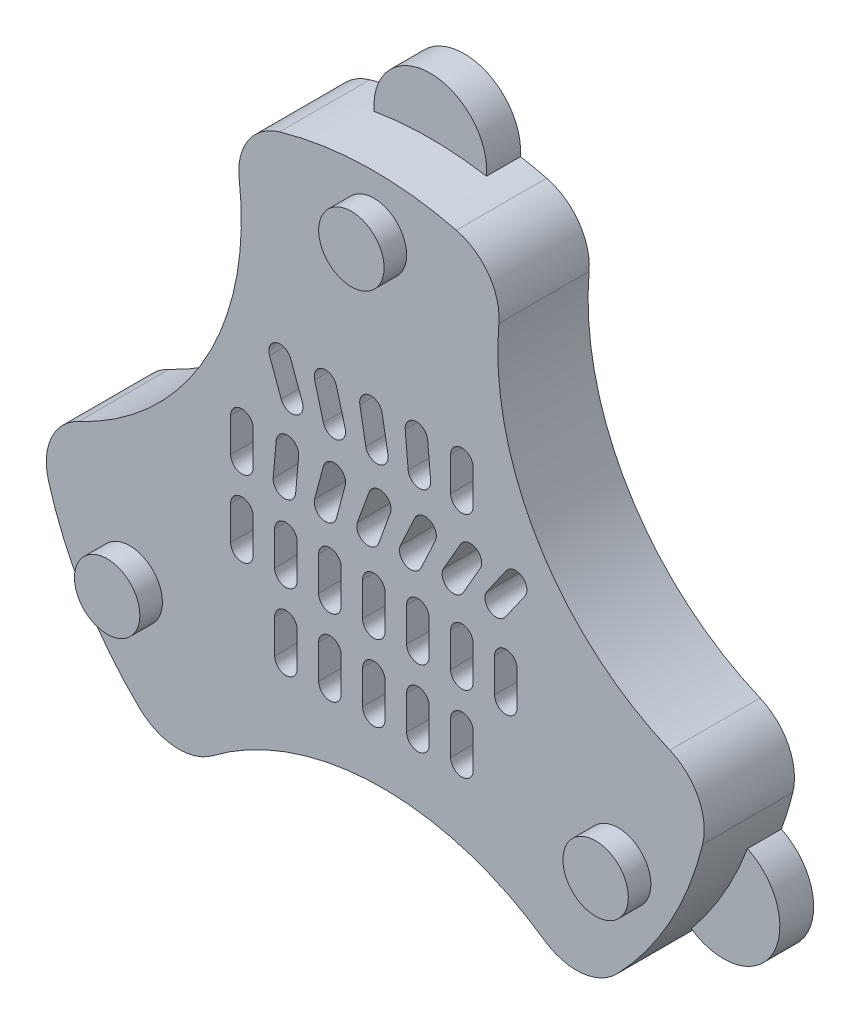
SolidWorks part; units mm, degrees
ref_plane "Спереди" through (0, 0, 0) normal (0, 0, 1) x (1, 0, 0)
ref_plane "Сверху" through (0, 0, 0) normal (0, 1, 0) x (1, 0, 0)
ref_plane "Справа" through (0, 0, 0) normal (1, 0, 0) x (0, 0, -1)
sketch "Sketch1" plane through (0, 0, 0) normal (0, 0, 1) x (1, 0, 0)
  line L0 (3.9, 6.755) -> (7.8, 0) construction
  line L2 (5.85, 10.1325) -> (11.7, 0) construction
  line L4 (7.8, 13.51) -> (15.6, 0) construction
  circle A61 centre (0, 0) radius 20
  circle A131 centre (0, 0) radius 1.25
  circle A484 centre (3.9, 0) radius 1.25
  circle A485 centre (7.8, 0) radius 1.25
  circle A486 centre (11.7, 0) radius 1.25
  circle A487 centre (15.6, 0) radius 1.25
  circle A488 centre (1.95, -3.3775) radius 1.25
  circle A489 centre (3.9, -6.755) radius 1.25
  circle A490 centre (5.85, -10.1325) radius 1.25
  circle A491 centre (7.8, -13.51) radius 1.25
  circle A492 centre (-1.95, -3.3775) radius 1.25
  circle A493 centre (-3.9, -6.755) radius 1.25
  circle A494 centre (-5.85, -10.1325) radius 1.25
  circle A495 centre (-7.8, -13.51) radius 1.25
  circle A496 centre (-3.9, 0) radius 1.25
  circle A497 centre (-7.8, 0) radius 1.25
  circle A498 centre (-11.7, 0) radius 1.25
  circle A499 centre (-15.6, 0) radius 1.25
  circle A500 centre (-1.95, 3.3775) radius 1.25
  circle A501 centre (-3.9, 6.755) radius 1.25
  circle A502 centre (-5.85, 10.1325) radius 1.25
  circle A503 centre (-7.8, 13.51) radius 1.25
  circle A504 centre (1.95, 3.3775) radius 1.25
  circle A505 centre (3.9, 6.755) radius 1.25
  circle A506 centre (5.85, 10.1325) radius 1.25
  circle A507 centre (7.8, 13.51) radius 1.25
  circle A508 centre (5.85, 3.3775) radius 1.25
  circle A509 centre (7.8, 6.755) radius 1.25
  circle A510 centre (9.75, 3.3775) radius 1.25
  circle A511 centre (11.7, 6.755) radius 1.25
  circle A512 centre (9.7491, 10.1341) radius 1.25
  circle A513 centre (13.6509, 3.3759) radius 1.25
  circle A514 centre (5.85, -3.3791) radius 1.25
  circle A515 centre (9.75, -3.3791) radius 1.25
  circle A516 centre (7.8, -6.7566) radius 1.25
  circle A517 centre (11.7, -6.7566) radius 1.25
  circle A518 centre (9.7491, -10.1356) radius 1.25
  circle A519 centre (13.6509, -3.3775) radius 1.25
  circle A520 centre (-0.0013, -6.7573) radius 1.25
  circle A521 centre (1.9487, -10.1348) radius 1.25
  circle A522 centre (-1.9513, -10.1348) radius 1.25
  circle A523 centre (-0.0013, -13.5123) radius 1.25
  circle A524 centre (-3.9032, -13.5123) radius 1.25
  circle A525 centre (3.9005, -13.5123) radius 1.25
  circle A526 centre (-5.8527, -3.3791) radius 1.25
  circle A527 centre (-7.8027, -6.7566) radius 1.25
  circle A528 centre (-9.7527, -3.3791) radius 1.25
  circle A529 centre (-11.7027, -6.7566) radius 1.25
  circle A530 centre (-13.6536, -3.3775) radius 1.25
  circle A531 centre (-9.7518, -10.1356) radius 1.25
  circle A532 centre (-5.8527, 3.3775) radius 1.25
  circle A533 centre (-9.7527, 3.3775) radius 1.25
  circle A534 centre (-7.8027, 6.755) radius 1.25
  circle A535 centre (-11.7027, 6.755) radius 1.25
  circle A536 centre (-9.7518, 10.1341) radius 1.25
  circle A537 centre (-13.6536, 3.3759) radius 1.25
  circle A538 centre (-0.0014, 6.7558) radius 1.25
  circle A539 centre (-1.9514, 10.1333) radius 1.25
  circle A540 centre (1.9486, 10.1333) radius 1.25
  circle A541 centre (-0.0014, 13.5108) radius 1.25
  circle A542 centre (3.9005, 13.5108) radius 1.25
  circle A543 centre (-3.9032, 13.5108) radius 1.25
  circle A544 centre (13.65, -1.1258) radius 2.2517 construction
  circle A545 centre (11.7009, -4.5044) radius 2.2522 construction
  circle A546 centre (9.75, -7.8834) radius 2.2522 construction
  circle A547 centre (7.7987, -11.2591) radius 2.2509 construction
  circle A548 centre (13.65, -1.1258) radius 0.65
  circle A549 centre (11.7009, -4.5044) radius 0.65
  circle A550 centre (9.75, -7.8834) radius 0.65
  circle A551 centre (7.7987, -11.2591) radius 0.65
  circle A552 centre (9.75, -1.1258) radius 0.65
  circle A553 centre (7.8009, -4.5044) radius 0.65
  circle A554 centre (5.85, -7.8834) radius 0.65
  circle A555 centre (3.8987, -11.2591) radius 0.65
  circle A556 centre (5.85, -1.1258) radius 0.65
  circle A557 centre (3.9009, -4.5044) radius 0.65
  circle A558 centre (1.95, -7.8834) radius 0.65
  circle A559 centre (-0.0013, -11.2591) radius 0.65
  circle A560 centre (1.95, -1.1258) radius 0.65
  circle A561 centre (0.0009, -4.5044) radius 0.65
  circle A562 centre (-1.95, -7.8834) radius 0.65
  circle A563 centre (-3.9013, -11.2591) radius 0.65
  circle A564 centre (-1.95, -1.1258) radius 0.65
  circle A565 centre (-3.8991, -4.5044) radius 0.65
  circle A566 centre (-5.85, -7.8834) radius 0.65
  circle A567 centre (-7.8013, -11.2591) radius 0.65
  circle A568 centre (-5.85, -1.1258) radius 0.65
  circle A569 centre (-7.7991, -4.5044) radius 0.65
  circle A570 centre (-9.75, -7.8834) radius 0.65
  circle A572 centre (-9.75, -1.1258) radius 0.65
  circle A573 centre (-11.6991, -4.5044) radius 0.65
  circle A576 centre (-13.65, -1.1258) radius 0.65
  circle A587 centre (0, 2.2517) radius 2.2517 construction
  circle A588 centre (0, 2.2517) radius 0.65
  circle A589 centre (3.9, 2.2517) radius 0.65
  circle A590 centre (7.8, 2.2517) radius 0.65
  circle A591 centre (11.7, 2.2517) radius 0.65
  circle A592 centre (15.6, 2.2517) radius 0.65
  circle A593 centre (1.9491, 5.6297) radius 2.2522 construction
  circle A594 centre (1.9491, 5.6297) radius 0.65
  circle A595 centre (5.8491, 5.6297) radius 0.65
  circle A596 centre (9.7491, 5.6297) radius 0.65
  circle A597 centre (13.6491, 5.6297) radius 0.65
  circle A598 centre (3.8991, 9.0072) radius 2.2522 construction
  circle A599 centre (3.8991, 9.0072) radius 0.65
  circle A600 centre (7.7991, 9.0072) radius 0.65
  circle A601 centre (11.6991, 9.0072) radius 0.65
  circle A602 centre (5.85, 12.3842) radius 2.2517 construction
  circle A603 centre (5.85, 12.3842) radius 0.65
  circle A604 centre (9.75, 12.3842) radius 0.65
  circle A605 centre (5.85, -14.6358) radius 0.65
  circle A606 centre (1.9509, -14.6353) radius 0.65
  circle A607 centre (-1.9491, -14.6353) radius 0.65
  circle A608 centre (-5.85, -14.6358) radius 0.65
  circle A609 centre (-15.6, 2.2517) radius 0.65
  circle A610 centre (-13.65, 5.6281) radius 0.65
  circle A611 centre (-11.7, 9.0056) radius 0.65
  circle A612 centre (-9.75, 12.3842) radius 0.65
  circle A613 centre (-5.85, 12.3842) radius 0.65
  circle A614 centre (-1.95, 12.3842) radius 0.65
  circle A615 centre (1.95, 12.3842) radius 0.65
  circle A616 centre (-7.8, 9.0056) radius 0.65
  circle A617 centre (-9.75, 5.6281) radius 0.65
  circle A618 centre (-11.7, 2.2517) radius 0.65
  circle A619 centre (-3.9, 9.0056) radius 0.65
  circle A620 centre (-5.85, 5.6281) radius 0.65
  circle A621 centre (-7.8, 2.2517) radius 0.65
  circle A622 centre (0, 9.0056) radius 0.65
  circle A623 centre (-1.95, 5.6281) radius 0.65
  circle A624 centre (-3.9, 2.2517) radius 0.65
  circle A625 centre (-15.5991, -4.5044) radius 0.65
  circle A626 centre (-13.65, -7.8834) radius 0.65
  circle A627 centre (-17.55, -7.8834) radius 0.65
  circle A628 centre (-19.5013, -11.2591) radius 0.65
  circle A629 centre (-15.6013, -11.2591) radius 0.65
  circle A630 centre (-11.7013, -11.2591) radius 0.65
  point P51 (0, 0)
  point P125 (-0.0013, -0.0008)
  point P231 (0, 0)
  dimension "D1" = 5
  dimension "D3" = 6
  dimension "D5" = 8
  dimension "D7" = 4
  dimension "D11" = 4
  dimension "D2" = 6
  dimension "D6" = 5
  dimension "D8" = 3
  dimension "D9" = 2
  dimension "D4" = 1.3
  dimension "D10" = 3
ref_plane "Plane1" through (0, 0, 10) normal (0, 0, 1) x (1, 0, 0)
sketch "Sketch2" plane through (0, 0, 10) normal (0, 0, 1) x (1, 0, 0)
  line L2 (8.0291, 21.9345) -> (-10.7971, 21.9345) construction
  circle A52 centre (0, 0) radius 16.85 construction
  circle A53 centre (0, 0) radius 18.85
  point P0 (0, 0)
  point P10 (0, 0)
  point P11 (0, 0)
  line B0 (4.7641, 11.7139) -> (5.0256, 8.7254)
  arc B1 (3.0332, 8.551) -> (5.0256, 8.7254) centre (4.0294, 8.6382) ccw
  line B2 (2.7717, 11.5396) -> (3.0332, 8.551)
  arc B3 (4.7641, 11.7139) -> (2.7717, 11.5396) centre (3.7679, 11.6268) ccw
  line B4 (3.7679, 11.6268) -> (4.0294, 8.6382) construction
  line B5 (0.722, 11.7838) -> (1.2429, 8.8293)
  arc B6 (-0.7267, 8.482) -> (1.2429, 8.8293) centre (0.2581, 8.6557) ccw
  line B7 (-1.2476, 11.4365) -> (-0.7267, 8.482)
  arc B8 (0.722, 11.7838) -> (-1.2476, 11.4365) centre (-0.2628, 11.6101) ccw
  line B9 (-0.2628, 11.6101) -> (0.2581, 8.6557) construction
  line B10 (-3.3247, 11.8406) -> (-2.5482, 8.9428)
  arc B11 (-4.48, 8.4252) -> (-2.5482, 8.9428) centre (-3.5141, 8.684) ccw
  line B12 (-5.2565, 11.323) -> (-4.48, 8.4252)
  arc B13 (-3.3247, 11.8406) -> (-5.2565, 11.323) centre (-4.2906, 11.5818) ccw
  line B14 (-4.2906, 11.5818) -> (-3.5141, 8.684) construction
  line B15 (-7.3747, 11.8841) -> (-6.3486, 9.065)
  arc B16 (-8.228, 8.3809) -> (-6.3486, 9.065) centre (-7.2883, 8.723) ccw
  line B17 (-9.2541, 11.2) -> (-8.228, 8.3809)
  arc B18 (-7.3747, 11.8841) -> (-9.2541, 11.2) centre (-8.3144, 11.542) ccw
  line B19 (-8.3144, 11.542) -> (-7.2883, 8.723) construction
  line B20 (10.0165, 2.7228) -> (11.7373, 5.1803)
  arc B21 (13.3756, 4.0332) -> (11.7373, 5.1803) centre (12.5564, 4.6067) ccw
  line B22 (11.6548, 1.5757) -> (13.3756, 4.0332)
  arc B23 (10.0165, 2.7228) -> (11.6548, 1.5757) centre (10.8357, 2.1493) ccw
  line B24 (10.8357, 2.1493) -> (12.5564, 4.6067) construction
  line B25 (6.18, 2.579) -> (7.68, 5.177)
  arc B26 (9.4121, 4.177) -> (7.68, 5.177) centre (8.546, 4.677) ccw
  line B27 (7.9121, 1.579) -> (9.4121, 4.177)
  arc B28 (6.18, 2.579) -> (7.9121, 1.579) centre (7.046, 2.079) ccw
  line B29 (7.046, 2.079) -> (8.546, 4.677) construction
  line B30 (2.3558, 2.4412) -> (3.6237, 5.1601)
  arc B31 (5.4363, 4.3148) -> (3.6237, 5.1601) centre (4.53, 4.7375) ccw
  line B32 (4.1684, 1.5959) -> (5.4363, 4.3148)
  arc B33 (2.3558, 2.4412) -> (4.1684, 1.5959) centre (3.2621, 2.0185) ccw
  line B34 (3.2621, 2.0185) -> (4.53, 4.7375) construction
  line B35 (-1.4567, 2.3105) -> (-0.4306, 5.1296)
  arc B36 (1.4488, 4.4455) -> (-0.4306, 5.1296) centre (0.5091, 4.7875) ccw
  line B37 (0.4227, 1.6264) -> (1.4488, 4.4455)
  arc B38 (-1.4567, 2.3105) -> (0.4227, 1.6264) centre (-0.517, 1.9685) ccw
  line B39 (-0.517, 1.9685) -> (0.5091, 4.7875) construction
  line B40 (-5.2581, 2.1879) -> (-4.4816, 5.0857)
  arc B41 (-2.5498, 4.5681) -> (-4.4816, 5.0857) centre (-3.5157, 4.8269) ccw
  line B42 (-3.3263, 1.6703) -> (-2.5498, 4.5681)
  arc B43 (-5.2581, 2.1879) -> (-3.3263, 1.6703) centre (-4.2922, 1.9291) ccw
  line B44 (-4.2922, 1.9291) -> (-3.5157, 4.8269) construction
  line B45 (-8.9296, 1.9704) -> (-8.6682, 4.9589)
  arc B46 (-6.6758, 4.7846) -> (-8.6682, 4.9589) centre (-7.672, 4.8718) ccw
  line B47 (-6.9372, 1.7961) -> (-6.6758, 4.7846)
  arc B48 (-8.9296, 1.9704) -> (-6.9372, 1.7961) centre (-7.9334, 1.8832) ccw
  line B49 (-7.9334, 1.8832) -> (-7.672, 4.8718) construction
  line B50 (-12.704, 1.878) -> (-12.704, 4.878)
  arc B51 (-10.704, 4.878) -> (-12.704, 4.878) centre (-11.704, 4.878) ccw
  line B52 (-10.704, 1.878) -> (-10.704, 4.878)
  arc B53 (-12.704, 1.878) -> (-10.704, 1.878) centre (-11.704, 1.878) ccw
  line B54 (-11.704, 1.878) -> (-11.704, 4.878) construction
  line B55 (10.6941, -4.8778) -> (10.6941, -1.8778)
  arc B56 (12.6941, -1.8778) -> (10.6941, -1.8778) centre (11.6941, -1.8778) ccw
  line B57 (12.6941, -4.8778) -> (12.6941, -1.8778)
  arc B58 (10.6941, -4.8778) -> (12.6941, -4.8778) centre (11.6941, -4.8778) ccw
  line B59 (6.7941, -4.8778) -> (6.7941, -1.8778)
  arc B60 (8.7941, -1.8778) -> (6.7941, -1.8778) centre (7.7941, -1.8778) ccw
  line B61 (8.7941, -4.8778) -> (8.7941, -1.8778)
  arc B62 (6.7941, -4.8778) -> (8.7941, -4.8778) centre (7.7941, -4.8778) ccw
  line B63 (2.8941, -4.8778) -> (2.8941, -1.8778)
  arc B64 (4.8941, -1.8778) -> (2.8941, -1.8778) centre (3.8941, -1.8778) ccw
  line B65 (4.8941, -4.8778) -> (4.8941, -1.8778)
  arc B66 (2.8941, -4.8778) -> (4.8941, -4.8778) centre (3.8941, -4.8778) ccw
  line B67 (-1.0059, -4.8778) -> (-1.0059, -1.8778)
  arc B68 (0.9941, -1.8778) -> (-1.0059, -1.8778) centre (-0.0059, -1.8778) ccw
  line B69 (0.9941, -4.8778) -> (0.9941, -1.8778)
  arc B70 (-1.0059, -4.8778) -> (0.9941, -4.8778) centre (-0.0059, -4.8778) ccw
  line B71 (-4.9059, -4.8778) -> (-4.9059, -1.8778)
  arc B72 (-2.9059, -1.8778) -> (-4.9059, -1.8778) centre (-3.9059, -1.8778) ccw
  line B73 (-2.9059, -4.8778) -> (-2.9059, -1.8778)
  arc B74 (-4.9059, -4.8778) -> (-2.9059, -4.8778) centre (-3.9059, -4.8778) ccw
  line B75 (-8.8046, -4.8778) -> (-8.8008, -1.8778)
  arc B76 (-6.8008, -1.8804) -> (-8.8008, -1.8778) centre (-7.8008, -1.8791) ccw
  line B77 (-6.8046, -4.8804) -> (-6.8008, -1.8804)
  arc B78 (-8.8046, -4.8778) -> (-6.8046, -4.8804) centre (-7.8046, -4.8791) ccw
  line B79 (-12.7059, -4.8778) -> (-12.7059, -1.8778)
  arc B80 (-10.7059, -1.8778) -> (-12.7059, -1.8778) centre (-11.7059, -1.8778) ccw
  line B81 (-10.7059, -4.8778) -> (-10.7059, -1.8778)
  arc B82 (-12.7059, -4.8778) -> (-10.7059, -4.8778) centre (-11.7059, -4.8778) ccw
  line B83 (8.7993, -8.6356) -> (8.7993, -11.6356)
  arc B84 (6.7993, -11.6356) -> (8.7993, -11.6356) centre (7.7993, -11.6356) ccw
  line B85 (6.7993, -8.6356) -> (6.7993, -11.6356)
  arc B86 (8.7993, -8.6356) -> (6.7993, -8.6356) centre (7.7993, -8.6356) ccw
  line B87 (4.8993, -8.6356) -> (4.8993, -11.6356)
  arc B88 (2.8993, -11.6356) -> (4.8993, -11.6356) centre (3.8993, -11.6356) ccw
  line B89 (2.8993, -8.6356) -> (2.8993, -11.6356)
  arc B90 (4.8993, -8.6356) -> (2.8993, -8.6356) centre (3.8993, -8.6356) ccw
  line B91 (0.9993, -8.6356) -> (0.9993, -11.6356)
  arc B92 (-1.0007, -11.6356) -> (0.9993, -11.6356) centre (-0.0007, -11.6356) ccw
  line B93 (-1.0007, -8.6356) -> (-1.0007, -11.6356)
  arc B94 (0.9993, -8.6356) -> (-1.0007, -8.6356) centre (-0.0007, -8.6356) ccw
  line B95 (-2.9007, -8.6356) -> (-2.9007, -11.6356)
  arc B96 (-4.9007, -11.6356) -> (-2.9007, -11.6356) centre (-3.9007, -11.6356) ccw
  line B97 (-4.9007, -8.6356) -> (-4.9007, -11.6356)
  arc B98 (-2.9007, -8.6356) -> (-4.9007, -8.6356) centre (-3.9007, -8.6356) ccw
  line B99 (-6.8007, -8.6356) -> (-6.8007, -11.6356)
  arc B100 (-8.8007, -11.6356) -> (-6.8007, -11.6356) centre (-7.8007, -11.6356) ccw
  line B101 (-8.8007, -8.6356) -> (-8.8007, -11.6356)
  arc B102 (-6.8007, -8.6356) -> (-8.8007, -8.6356) centre (-7.8007, -8.6356) ccw
  line B103 (8.7976, 11.6329) -> (8.7976, 8.6329)
  arc B104 (6.7976, 8.6329) -> (8.7976, 8.6329) centre (7.7976, 8.6329) ccw
  line B105 (6.7976, 11.6329) -> (6.7976, 8.6329)
  arc B106 (8.7976, 11.6329) -> (6.7976, 11.6329) centre (7.7976, 11.6329) ccw
  dimension "D15" = 2
  dimension "D2" = 95
  dimension "D4" = 105
  dimension "D5" = 110
  dimension "D6" = 55
  dimension "D7" = 60
  dimension "D9" = 70
  dimension "D12" = 90
  dimension "D3" = 100
  dimension "D8" = 65
  dimension "D10" = 75
  dimension "D11" = 85
sketch_block_instance "Block4-1"
sketch_block "Block4"
sketch_block_instance "Block5-1"
sketch_block "Block5"
sketch_block_instance "Block6-1"
sketch_block "Block6"
sketch_block_instance "Block7-1"
sketch_block "Block7" parameters "D1"=2, "D2"=3
sketch_block_instance "Block8-1"
sketch_block "Block8"
sketch_block_instance "Block9-1"
sketch_block "Block9"
sketch_block_instance "Block10-1"
sketch_block "Block10"
sketch_block_instance "Block11-1"
sketch_block "Block11"
sketch_block_instance "Block12-1"
sketch_block "Block12"
sketch_block_instance "Block13-1"
sketch_block "Block13" parameters "D1"=2, "D2"=3
sketch_block_instance "Block14-1"
sketch_block "Block14"
sketch_block_instance "Block15-1"
sketch_block "Block15"
sketch_block_instance "Block16-1"
sketch_block "Block16"
sketch_block_instance "Block17-1"
sketch_block "Block17"
sketch_block_instance "Block18-1"
sketch_block "Block18"
sketch_block_instance "Block19-1"
sketch_block "Block19"
sketch_block_instance "Block20-1"
sketch_block "Block20" parameters "D1"=3, "D2"=2
sketch_block_instance "Block21-1"
sketch_block "Block21"
sketch_block_instance "Block22-1"
sketch_block "Block22"
sketch_block_instance "Block23-1"
sketch_block "Block23"
sketch_block_instance "Block24-1"
sketch_block "Block24"
sketch_block_instance "Block25-1"
sketch_block "Block25"
sketch_block_instance "Block26-1"
sketch_block "Block26" parameters "D1"=3, "D2"=2
sketch_block_instance "Block28-1"
sketch_block "Block28"
extrude "Boss-Extrude1" add sketch "Sketch2" along normal blind 8
sketch "Sketch3" plane through (0, 0, 18) normal (0, 0, 1) x (1, 0, 0)
  circle A0 centre (0, 0) radius 17.6
  circle A1 centre (0, 0) radius 30
extrude "Boss-Extrude2" add sketch "Sketch3" against normal up to surface (8 mm away) up to face at (-7.8007, -10.1356, 10)
sketch "Sketch4" plane through (0, 0, 18) normal (0, 0, 1) x (1, 0, 0)
  circle A0 centre (0, 0) radius 25 construction
  circle A1 centre (0, 25) radius 2.9
  circle A2 centre (21.6506, -12.5) radius 2.9
  circle A3 centre (-21.6506, -12.5) radius 2.9
  point P11 (0, 0)
  dimension "D1" = 3
extrude "Boss-Extrude3" add sketch "Sketch4" along normal blind 2
sketch "Sketch6" plane through (0, 0, 10) normal (0, 0, -1) x (-1, 0, 0)
  circle A0 centre (0, 30) radius 5
  circle A1 centre (0, 0) radius 30 construction
  circle A2 centre (25.9808, -15) radius 5
  circle A3 centre (-25.9808, -15) radius 5
  point P10 (0, 0)
  dimension "D1" = 3
extrude "Boss-Extrude4" add sketch "Sketch6" against normal blind 3
sketch "Sketch5" plane through (0, 0, 10) normal (0, 0, -1) x (-1, 0, 0)
  circle A0 centre (0, 25) radius 3
  circle A1 centre (21.6506, -12.5) radius 3
  circle A2 centre (-21.6506, -12.5) radius 3
extrude "Cut-Extrude1" cut sketch "Sketch5" against normal blind 3
sketch "Sketch7" plane through (0, 0, 10) normal (0, 0, -1) x (-1, 0, 0)
  line L0 (0, 0) -> (-35.9801, 21.6664) construction
  circle A0 centre (0, 0) radius 42 construction
  circle A1 centre (-35.9801, 21.6664) radius 25
  circle A2 centre (36.7537, 20.3265) radius 25
  circle A3 centre (-0.7736, -41.9929) radius 25
  point P11 (0, 0)
  dimension "D1" = 3
extrude "Cut-Extrude2" cut sketch "Sketch7" against normal blind 8
fillet "Fillet1" radius 5 6 edges at (-29.7735, -3.6793, 14) (-12.7099, 27.1746, 14) (18.0731, -23.945, 14) (-17.1789, -24.5944, 14) (11.7004, 27.6243, 14) (29.8888, -2.5802, 14)
sketch "Sketch8"
sketch_block_instance "Block1-1"
sketch_block "Block1" parameters "D1"=2, "D2"=3
sketch_block_instance "Block3-1"
sketch_block "Block3" parameters "D1"=2, "D2"=3
sketch "Sketch9" plane through (0, 0, 0) normal (0, 0, 1) x (1, 0, 0)
  line L0 (-7.8, 13.51) -> (-7.8027, 6.755) construction
  line L1 (-9.7518, 10.1341) -> (-5.85, 10.1325) construction
  line L2 (-7.8008, 11.6325) -> (-7.8019, 8.6325) construction
  line L3 (-6.8008, 11.6321) -> (-6.8019, 8.6321)
  line L4 (-8.8008, 11.6329) -> (-8.8019, 8.6329)
  line L5 (-4.9008, 11.6329) -> (-4.9019, 8.6329)
  line L6 (-2.9008, 11.6321) -> (-2.9019, 8.6321)
  line L7 (-3.9008, 11.6325) -> (-3.9019, 8.6325) construction
  line L8 (-1.0008, 11.6329) -> (-1.0019, 8.6329)
  line L9 (0.9992, 11.6321) -> (0.9981, 8.6321)
  line L10 (-0.0008, 11.6325) -> (-0.0019, 8.6325) construction
  line L11 (2.8992, 11.6329) -> (2.8981, 8.6329)
  line L12 (4.8992, 11.6321) -> (4.8981, 8.6321)
  line L13 (3.8992, 11.6325) -> (3.8981, 8.6325) construction
  line L14 (6.7992, 11.6329) -> (6.7981, 8.6329)
  line L15 (8.7992, 11.6321) -> (8.7981, 8.6321)
  line L16 (7.7992, 11.6325) -> (7.7981, 8.6325) construction
  line L17 (-9.7518, 10.1341) -> (-9.7527, 3.3775) construction
  line L18 (-11.7027, 6.755) -> (-7.8027, 6.755) construction
  line L19 (-10.7035, 1.877) -> (-10.702, 4.877)
  line L22 (-9.7527, 3.3775) -> (-5.8527, 3.3775) construction
  line L25 (-7.8027, 6.755) -> (-7.8, 0) construction
  line L26 (-7.8035, 1.8775) -> (-7.8019, 4.8775) construction
  line L27 (-8.8035, 1.878) -> (-8.8019, 4.878)
  line L28 (-6.8035, 1.877) -> (-6.8019, 4.877)
  line L29 (-2.9035, 1.877) -> (-2.9019, 4.877)
  line L30 (-4.9035, 1.878) -> (-4.9019, 4.878)
  line L31 (-3.9035, 1.8775) -> (-3.9019, 4.8775) construction
  line L32 (0.9965, 1.877) -> (0.9981, 4.877)
  line L33 (-1.0035, 1.878) -> (-1.0019, 4.878)
  line L34 (-0.0035, 1.8775) -> (-0.0019, 4.8775) construction
  line L35 (4.8965, 1.877) -> (4.8981, 4.877)
  line L36 (2.8965, 1.878) -> (2.8981, 4.878)
  line L37 (3.8965, 1.8775) -> (3.8981, 4.8775) construction
  line L38 (8.7965, 1.877) -> (8.7981, 4.877)
  line L39 (6.7965, 1.878) -> (6.7981, 4.878)
  line L40 (7.7965, 1.8775) -> (7.7981, 4.8775) construction
  line L41 (12.6965, 1.877) -> (12.6981, 4.877)
  line L42 (10.6965, 1.878) -> (10.6981, 4.878)
  line L43 (11.6965, 1.8775) -> (11.6981, 4.8775) construction
  line L44 (-12.7035, 1.878) -> (-12.7019, 4.878)
  line L45 (-11.7035, 1.8775) -> (-11.702, 4.8775) construction
  line L46 (-9.7527, -3.3791) -> (-5.8527, -3.3791) construction
  line L47 (-7.8, 0) -> (-7.8027, -6.7566) construction
  line L48 (-7.8046, -4.8791) -> (-7.8008, -1.8791) construction
  line L49 (-8.8046, -4.8778) -> (-8.8008, -1.8778)
  line L50 (-6.8046, -4.8804) -> (-6.8008, -1.8804)
  line L51 (-2.9046, -4.8804) -> (-2.9008, -1.8804)
  line L52 (-4.9046, -4.8778) -> (-4.9008, -1.8778)
  line L53 (-3.9046, -4.8791) -> (-3.9008, -1.8791) construction
  line L54 (0.9954, -4.8804) -> (0.9992, -1.8804)
  line L55 (-1.0046, -4.8778) -> (-1.0008, -1.8778)
  line L56 (-0.0046, -4.8791) -> (-0.0008, -1.8791) construction
  line L57 (4.8954, -4.8804) -> (4.8992, -1.8804)
  line L58 (2.8954, -4.8778) -> (2.8992, -1.8778)
  line L59 (3.8954, -4.8791) -> (3.8992, -1.8791) construction
  line L60 (8.7954, -4.8804) -> (8.7992, -1.8804)
  line L61 (6.7954, -4.8778) -> (6.7992, -1.8778)
  line L62 (7.7954, -4.8791) -> (7.7992, -1.8791) construction
  line L63 (12.6954, -4.8804) -> (12.6992, -1.8804)
  line L64 (10.6954, -4.8778) -> (10.6992, -1.8778)
  line L65 (11.6954, -4.8791) -> (11.6992, -1.8791) construction
  line L66 (-10.7046, -4.8804) -> (-10.7008, -1.8804)
  line L67 (-12.7046, -4.8778) -> (-12.7008, -1.8778)
  line L68 (-11.7046, -4.8791) -> (-11.7008, -1.8791) construction
  line L69 (-9.7518, -10.1356) -> (-5.482, -10.1356) construction
  line L70 (-7.8027, -6.7566) -> (-7.8, -13.51) construction
  line L71 (-7.8007, -8.6356) -> (-7.8007, -11.6356) construction
  line L72 (-6.8007, -8.6356) -> (-6.8007, -11.6356)
  line L73 (-8.8007, -8.6356) -> (-8.8007, -11.6356)
  line L74 (-4.9007, -8.6356) -> (-4.9007, -11.6356)
  line L75 (-2.9007, -8.6356) -> (-2.9007, -11.6356)
  line L76 (-3.9007, -8.6356) -> (-3.9007, -11.6356) construction
  line L77 (-1.0007, -8.6356) -> (-1.0007, -11.6356)
  line L78 (0.9993, -8.6356) -> (0.9993, -11.6356)
  line L79 (-0.0007, -8.6356) -> (-0.0007, -11.6356) construction
  line L80 (2.8993, -8.6356) -> (2.8993, -11.6356)
  line L81 (4.8993, -8.6356) -> (4.8993, -11.6356)
  line L82 (3.8993, -8.6356) -> (3.8993, -11.6356) construction
  line L83 (6.7993, -8.6356) -> (6.7993, -11.6356)
  line L84 (8.7993, -8.6356) -> (8.7993, -11.6356)
  line L85 (7.7993, -8.6356) -> (7.7993, -11.6356) construction
  arc A0 (-6.8008, 11.6321) -> (-8.8008, 11.6329) centre (-7.8008, 11.6325) ccw
  arc A1 (-8.8019, 8.6329) -> (-6.8019, 8.6321) centre (-7.8019, 8.6325) ccw
  arc A2 (-2.9008, 11.6321) -> (-4.9008, 11.6329) centre (-3.9008, 11.6325) ccw
  arc A3 (-4.9019, 8.6329) -> (-2.9019, 8.6321) centre (-3.9019, 8.6325) ccw
  arc A4 (0.9992, 11.6321) -> (-1.0008, 11.6329) centre (-0.0008, 11.6325) ccw
  arc A5 (-1.0019, 8.6329) -> (0.9981, 8.6321) centre (-0.0019, 8.6325) ccw
  arc A6 (4.8992, 11.6321) -> (2.8992, 11.6329) centre (3.8992, 11.6325) ccw
  arc A7 (2.8981, 8.6329) -> (4.8981, 8.6321) centre (3.8981, 8.6325) ccw
  arc A8 (8.7992, 11.6321) -> (6.7992, 11.6329) centre (7.7992, 11.6325) ccw
  arc A9 (6.7981, 8.6329) -> (8.7981, 8.6321) centre (7.7981, 8.6325) ccw
  arc A14 (-8.8035, 1.878) -> (-6.8035, 1.877) centre (-7.8035, 1.8775) ccw
  arc A15 (-6.8019, 4.877) -> (-8.8019, 4.878) centre (-7.8019, 4.8775) ccw
  arc A16 (-4.9035, 1.878) -> (-2.9035, 1.877) centre (-3.9035, 1.8775) ccw
  arc A17 (-2.9019, 4.877) -> (-4.9019, 4.878) centre (-3.9019, 4.8775) ccw
  arc A18 (-1.0035, 1.878) -> (0.9965, 1.877) centre (-0.0035, 1.8775) ccw
  arc A19 (0.9981, 4.877) -> (-1.0019, 4.878) centre (-0.0019, 4.8775) ccw
  arc A20 (2.8965, 1.878) -> (4.8965, 1.877) centre (3.8965, 1.8775) ccw
  arc A21 (4.8981, 4.877) -> (2.8981, 4.878) centre (3.8981, 4.8775) ccw
  arc A22 (6.7965, 1.878) -> (8.7965, 1.877) centre (7.7965, 1.8775) ccw
  arc A23 (8.7981, 4.877) -> (6.7981, 4.878) centre (7.7981, 4.8775) ccw
  arc A24 (10.6965, 1.878) -> (12.6965, 1.877) centre (11.6965, 1.8775) ccw
  arc A25 (12.6981, 4.877) -> (10.6981, 4.878) centre (11.6981, 4.8775) ccw
  arc A26 (-12.7035, 1.878) -> (-10.7035, 1.877) centre (-11.7035, 1.8775) ccw
  arc A27 (-10.702, 4.877) -> (-12.7019, 4.878) centre (-11.702, 4.8775) ccw
  arc A28 (-8.8046, -4.8778) -> (-6.8046, -4.8804) centre (-7.8046, -4.8791) ccw
  arc A29 (-6.8008, -1.8804) -> (-8.8008, -1.8778) centre (-7.8008, -1.8791) ccw
  arc A30 (-4.9046, -4.8778) -> (-2.9046, -4.8804) centre (-3.9046, -4.8791) ccw
  arc A31 (-2.9008, -1.8804) -> (-4.9008, -1.8778) centre (-3.9008, -1.8791) ccw
  arc A32 (-1.0046, -4.8778) -> (0.9954, -4.8804) centre (-0.0046, -4.8791) ccw
  arc A33 (0.9992, -1.8804) -> (-1.0008, -1.8778) centre (-0.0008, -1.8791) ccw
  arc A34 (2.8954, -4.8778) -> (4.8954, -4.8804) centre (3.8954, -4.8791) ccw
  arc A35 (4.8992, -1.8804) -> (2.8992, -1.8778) centre (3.8992, -1.8791) ccw
  arc A36 (6.7954, -4.8778) -> (8.7954, -4.8804) centre (7.7954, -4.8791) ccw
  arc A37 (8.7992, -1.8804) -> (6.7992, -1.8778) centre (7.7992, -1.8791) ccw
  arc A38 (10.6954, -4.8778) -> (12.6954, -4.8804) centre (11.6954, -4.8791) ccw
  arc A39 (12.6992, -1.8804) -> (10.6992, -1.8778) centre (11.6992, -1.8791) ccw
  arc A40 (-12.7046, -4.8778) -> (-10.7046, -4.8804) centre (-11.7046, -4.8791) ccw
  arc A41 (-10.7008, -1.8804) -> (-12.7008, -1.8778) centre (-11.7008, -1.8791) ccw
  arc A42 (-6.8007, -8.6356) -> (-8.8007, -8.6356) centre (-7.8007, -8.6356) ccw
  arc A43 (-8.8007, -11.6356) -> (-6.8007, -11.6356) centre (-7.8007, -11.6356) ccw
  arc A44 (-2.9007, -8.6356) -> (-4.9007, -8.6356) centre (-3.9007, -8.6356) ccw
  arc A45 (-4.9007, -11.6356) -> (-2.9007, -11.6356) centre (-3.9007, -11.6356) ccw
  arc A46 (0.9993, -8.6356) -> (-1.0007, -8.6356) centre (-0.0007, -8.6356) ccw
  arc A47 (-1.0007, -11.6356) -> (0.9993, -11.6356) centre (-0.0007, -11.6356) ccw
  arc A48 (4.8993, -8.6356) -> (2.8993, -8.6356) centre (3.8993, -8.6356) ccw
  arc A49 (2.8993, -11.6356) -> (4.8993, -11.6356) centre (3.8993, -11.6356) ccw
  arc A50 (8.7993, -8.6356) -> (6.7993, -8.6356) centre (7.7993, -8.6356) ccw
  arc A51 (6.7993, -11.6356) -> (8.7993, -11.6356) centre (7.7993, -11.6356) ccw
  circle A52 centre (0, 0) radius 16.85 construction
  circle A53 centre (0, 0) radius 18.85
  point P10 (-7.8014, 10.1325)
  point P18 (-3.9014, 10.1325)
  point P25 (-0.0014, 10.1325)
  point P32 (3.8986, 10.1325)
  point P39 (7.7986, 10.1325)
  point P50 (-11.7027, 3.3775)
  point P58 (-7.8027, 3.3775)
  point P68 (-3.9027, 3.3775)
  point P75 (-0.0027, 3.3775)
  point P82 (3.8973, 3.3775)
  point P89 (7.7973, 3.3775)
  point P96 (11.6973, 3.3775)
  point P108 (-7.8027, -3.3791)
  point P116 (-3.9027, -3.3791)
  point P123 (-0.0027, -3.3791)
  point P130 (3.8973, -3.3791)
  point P137 (7.7973, -3.3791)
  point P144 (11.6973, -3.3791)
  point P151 (-11.7027, -3.3791)
  point P162 (-7.8007, -10.1356)
  point P170 (-3.9007, -10.1356)
  point P177 (-0.0007, -10.1356)
  point P184 (3.8993, -10.1356)
  point P191 (7.7993, -10.1356)
  dimension "D1" = 2
  dimension "D15" = 2
  dimension "D2" = 3
  dimension "D4" = 2
  dimension "D5" = 3
  dimension "D6" = 2
  dimension "D7" = 3
  dimension "D9" = 2
  dimension "D12" = 3
  dimension "D13" = 2
  dimension "D3" = 5
  dimension "D8" = 6
  dimension "D10" = 6
  dimension "D11" = 2
  dimension "D14" = 5
